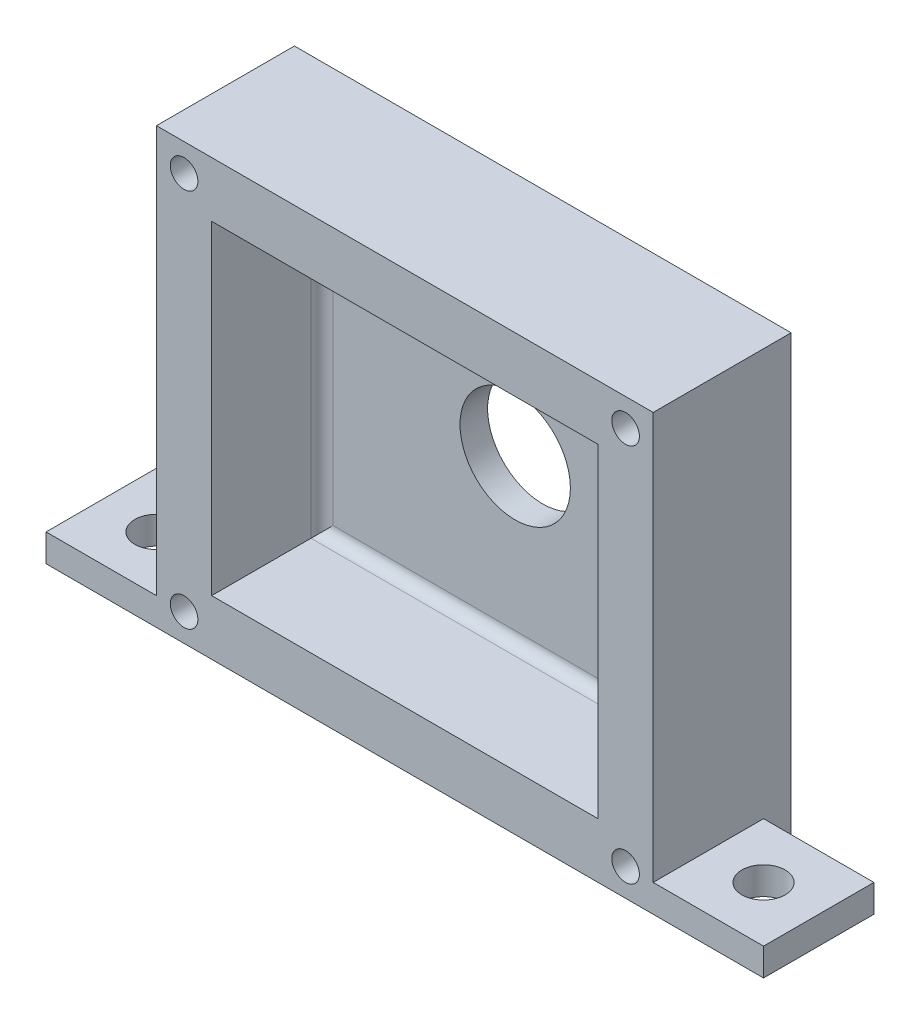
SolidWorks part; units mm, degrees
ref_plane "Front Plane" through (0, 0, 0) normal (0, 0, 1) x (1, 0, 0)
ref_plane "Top Plane" through (0, 0, 0) normal (0, 1, 0) x (1, 0, 0)
ref_plane "Right Plane" through (0, 0, 0) normal (1, 0, 0) x (0, 0, -1)
sketch "Sketch1" plane through (0, 0, 0) normal (0, 0, 1) x (1, 0, 0)
  line L1 (22.225, -18.6531) -> (-22.225, -18.6531)
  line L2 (22.225, -18.6531) -> (22.225, 18.6531)
  line L3 (22.225, 18.6531) -> (-22.225, 18.6531)
  line L4 (-22.225, -18.6531) -> (-22.225, 18.6531)
  line L5 (22.225, -18.6531) -> (-22.225, 18.6531) construction
  line L6 (22.225, 18.6531) -> (-22.225, -18.6531) construction
  line L7 (28.575, -25.0031) -> (-28.575, -25.0031)
  line L8 (28.575, -25.0031) -> (28.575, 25.0031)
  line L9 (28.575, 25.0031) -> (-28.575, 25.0031)
  line L10 (-28.575, -25.0031) -> (-28.575, 25.0031)
  line L11 (28.575, -25.0031) -> (-28.575, 25.0031) construction
  line L12 (28.575, 25.0031) -> (-28.575, -25.0031) construction
  point P0 (0, 0)
  point P6 (0, 0)
  dimension "D1" = 6.35
  dimension "D2" = 6.35
  dimension "D3" = 44.45
  dimension "D4" = 37.3062
extrude "Boss-Extrude1" add sketch "Sketch1" along normal blind 12.7
sketch "Sketch2" plane through (0, 0, 0) normal (0, 0, 1) x (1, 0, 0)
  line L1 (28.575, -25.0031) -> (-28.575, -25.0031)
  line L2 (28.575, -25.0031) -> (28.575, 25.0031)
  line L3 (28.575, 25.0031) -> (-28.575, 25.0031)
  line L4 (-28.575, -25.0031) -> (-28.575, 25.0031)
  line L5 (28.575, -25.0031) -> (-28.575, 25.0031) construction
  line L6 (28.575, 25.0031) -> (-28.575, -25.0031) construction
  circle A0 centre (0, 0) radius 6.35
  point P0 (0, 0)
  dimension "D1" = 12.7
extrude "Boss-Extrude2" add sketch "Sketch2" against normal blind 3.175
sketch "Sketch4" plane through (0, 0, 0) normal (0, 0, 1) x (1, 0, 0)
  line L1 (-28.575, -25.0031) -> (-41.275, -25.0031)
  line L2 (-28.575, -25.0031) -> (-28.575, -21.8281)
  line L3 (-28.575, -21.8281) -> (-41.275, -21.8281)
  line L4 (-41.275, -25.0031) -> (-41.275, -21.8281)
  line L5 (28.575, -25.0031) -> (41.275, -25.0031)
  line L6 (28.575, -25.0031) -> (28.575, -21.8281)
  line L7 (28.575, -21.8281) -> (41.275, -21.8281)
  line L8 (41.275, -25.0031) -> (41.275, -21.8281)
  dimension "D1" = 3.175
  dimension "D2" = 12.7
extrude "Boss-Extrude3" add sketch "Sketch4" along direction (0, 0, 1) on the side of the normal blind 12.7
sketch "Sketch5" plane through (0, -21.8281, 0) normal (0, 1, 0) x (1, 0, 0)
  line L0 (-41.275, 0) -> (-28.575, -12.7) construction
  line L1 (-28.575, -12.7) -> (-28.575, 0) construction
  line L2 (-28.575, 0) -> (-41.275, -12.7) construction
  line L3 (28.575, 0) -> (41.275, -12.7) construction
  line L4 (41.275, 0) -> (28.575, -12.7) construction
  circle A0 centre (-34.925, -6.35) radius 2.4892
  circle A1 centre (34.925, -6.35) radius 2.4892
  point P16 (-34.925, -6.35)
  point P17 (34.925, -6.35)
  dimension "D1" = 4.9784
  dimension "D2" = 4.9784
extrude "Cut-Extrude1" cut sketch "Sketch5" against normal blind 3.175
fillet "Fillet1" radius 1.27 4 edges at (0, -18.6531, 0) (22.225, 0, 0) (0, 18.6531, 0) (-22.225, 0, 0)
sketch "Sketch6" plane through (0, 0, 12.7) normal (0, 0, 1) x (1, 0, 0)
  line L0 (-28.575, 21.8281) -> (28.575, 21.8281) construction
  line L1 (-28.575, 25.0031) -> (-28.575, -21.8281) construction
  line L2 (28.575, -21.8281) -> (28.575, 25.0031) construction
  line L3 (26.9875, -21.8281) -> (-26.9875, -21.8281) construction
  line L6 (28.575, 25.0031) -> (-28.575, 25.0031) construction
  line L7 (25.4, 21.8281) -> (25.4, -21.8281) construction
  line L8 (25.4, -21.8281) -> (24.196, -20.7934) construction
  line L9 (-25.4, 21.8281) -> (-25.4, -21.8281) construction
  line L10 (-41.275, -25.0031) -> (41.275, -25.0031) construction
  line L11 (-24.196, 20.7934) -> (-25.4, 21.8281) construction
  circle A0 centre (-25.4, 21.8281) radius 1.5875
  circle A1 centre (25.4, 21.8281) radius 1.5875
  circle A2 centre (25.4, -21.8281) radius 1.5875
  circle A3 centre (-25.4, -21.8281) radius 1.5875
  dimension "D2" = 3.175
  dimension "D4" = 3.175
  dimension "D1" = 3.175
  dimension "D3" = 3.175
  dimension "D5" = 3.175
extrude "Cut-Extrude2" cut sketch "Sketch6" against normal blind 9.525
